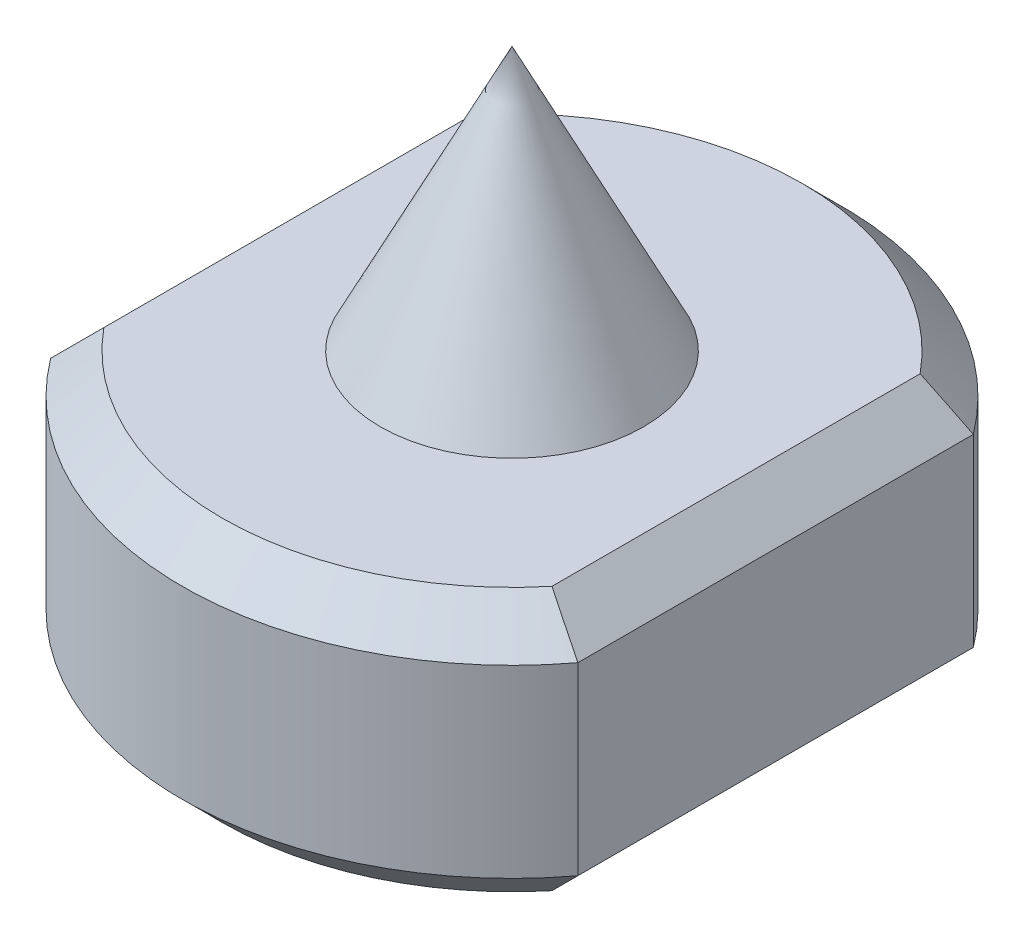
SolidWorks part; units mm, degrees
material "Custom Plastic"
ref_plane "Front Plane" through (0, 0, 0) normal (0, 0, 1) x (1, 0, 0)
ref_plane "Top Plane" through (0, 0, 0) normal (0, 1, 0) x (1, 0, 0)
ref_plane "Right Plane" through (0, 0, 0) normal (1, 0, 0) x (0, 0, -1)
sketch "Sketch1" plane through (0, 0, 0) normal (0, 1, 0) x (1, 0, 0)
  circle A0 centre (0, 0) radius 12.5
  dimension "D1" = 25
extrude "Boss-Extrude2" add sketch "Sketch1" along normal blind 10 contours A0
sketch "Sketch2" plane through (0, 0, 0) normal (0, 0, 1) x (1, 0, 0)
  line L0 (0, -1000) -> (0, 49000) construction
  line L1 (-12.5, 0) -> (12.5, 0) construction
  line L2 (5, 10) -> (0, 20)
  line L3 (0, 20) -> (0, 10)
  line L7 (12.5, 10) -> (-12.5, 10) construction
  line L8 (5, 10) -> (0, 10)
  point P5 (0, 0)
  point P7 (5, 14.1679)
  point P8 (0, 0)
  point P14 (5, 10)
  dimension "D1" = 10
  dimension "D2" = 5
revolve "Revolve1" add sketch "Sketch2" angle 360 about L0
sketch "Sketch3" plane through (0, 0, 0) normal (0, 1, 0) x (1, 0, 0)
  line L0 (0, -1000) -> (0, 49000) construction
  line L1 (-10, 7.5) -> (-10, -7.5)
  line L2 (10, 7.5) -> (10, -7.5)
  circle A0 centre (0, 0) radius 12.5 construction
  arc A1 (-10, 7.5) -> (-10, -7.5) centre (0, 0) ccw
  arc A2 (10, -7.5) -> (10, 7.5) centre (0, 0) ccw
  dimension "D1" = 20
extrude "Cut-Extrude1" cut sketch "Sketch3" along normal up to next
chamfer "Chamfer1" distance 1.5 angle 45 8 edges at (0, 0, -12.5) (0, 0, 12.5) (10, 0, 0) (-10, 0, 0) (-10, 10, 0) (0, 10, -12.5) (0, 10, 12.5) (10, 10, 0)
